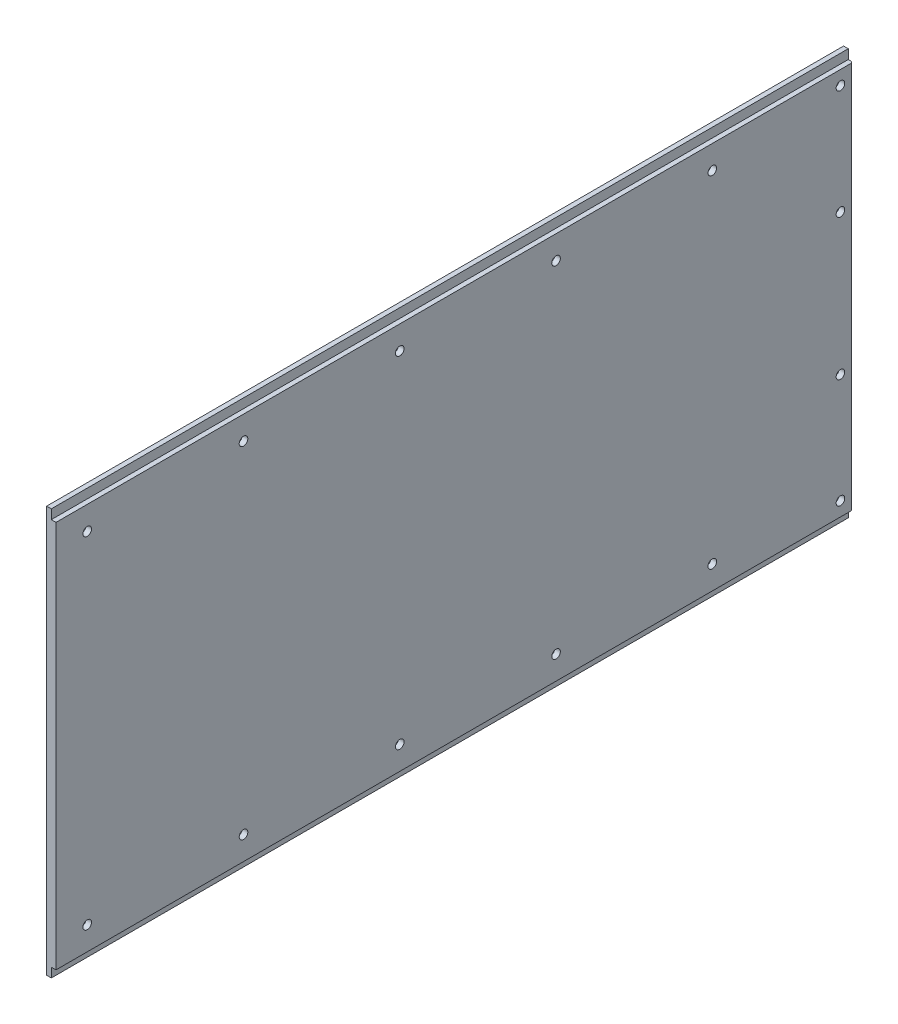
SolidWorks part; units mm, degrees
material "1060 Legierung"
ref_plane "Front Plane" through (0, 0, 0) normal (0, 0, 1) x (1, 0, 0)
ref_plane "Top Plane" through (0, 0, 0) normal (0, 1, 0) x (1, 0, 0)
ref_plane "Right Plane" through (0, 0, 0) normal (1, 0, 0) x (0, 0, -1)
sketch "Sketch1" plane through (0, 0, 0) normal (1, 0, 0) x (0, 0, -1)
  line L0 (0, 0) -> (59.3183, 0) construction
  line L1 (0, 28.1909) -> (0, -28.8956) construction
  line L2 (-255, 130) -> (255, 130)
  line L3 (255, 130) -> (255, -130)
  line L4 (255, -130) -> (-255, -130)
  line L5 (-255, -130) -> (-255, 130)
  dimension "D1" = 510
  dimension "D2" = 260
extrude "Boss-Extrude1" add sketch "Sketch1" along normal blind 6
sketch "Skizze2" plane through (0, 0, 255) normal (0, 0, 1) x (1, 0, 0)
  line L0 (21.4169, 0) -> (-13.9476, 0) construction
  line L1 (3, 130) -> (3, 124)
  line L2 (6, -130) -> (3, -130)
  line L3 (6, -130) -> (6, -124)
  line L4 (6, -124) -> (3, -124)
  line L5 (3, -130) -> (3, -124)
  line L6 (6, 124) -> (3, 124)
  line L7 (6, 130) -> (6, 124)
  line L8 (6, 130) -> (3, 130)
  dimension "D1" = 6
  dimension "D2" = 3
extrude "Schnitt-Linear austragen1" cut sketch "Skizze2" against normal through all
hole_wizard "Formsenkung fur M5 Linsensenkschraube mit Schlitz1" positions "Skizze6" profile "Skizze5" countersink size "M5" standard "Din" end condition through all
sketch "Skizze6" plane through (0, 0, 0) normal (-1, 0, 0) x (0, 0, 1)
  line L0 (-472.3808, 0) -> (85.2194, 0) construction
  line L2 (-255, -130) -> (-255, 130) construction
  point P0 (-247, 115)
  point P2 (-247, 45)
  dimension "D1" = 45
  dimension "D2" = 115
  dimension "D3" = 8
  dimension "D4" = 8
sketch "Skizze5" plane through (0, 115, -247) normal (0, 1, 0) x (0, 0, 1)
  line L0 (0, 0) -> (0, 6)
  line L1 (0, 6) -> (2.75, 6)
  line L2 (2.75, 6) -> (2.75, 2.45)
  line L3 (2.75, 2.45) -> (5.2, 0)
  line L5 (5.2, 0) -> (0, 0)
  line L6 (-2.75, 2.45) -> (-5.2, 0) construction
  line L11 (0, -6.35) -> (0, 107.95) construction
  dimension "Bohrerdurchmesser" = 5.5
  dimension "Bohrungstiefe" = 6
  dimension "Senkdurchmesser (Oben)" = 10.4
  dimension "Senkwinkel (Oben)" = 90
mirror "Spiegeln1" about plane through (0, 0, 0) normal (0, 1, 0) of "Formsenkung fur M5 Linsensenkschraube mit Schlitz1"
chamfer "Chamfer1" distance 1 angle 45 1 edges at (6, 0, -255)
hole_wizard "CSK for M5 Countersunk Raised Head Screw1" positions "Sketch3" profile "Sketch2" countersink size "M5" standard "DIN" end condition through all
sketch "Sketch3" plane through (0, 0, 0) normal (-1, 0, 0) x (0, 0, 1)
  line L0 (255, -130) -> (-255, -130) construction
  line L1 (255, 130) -> (255, -130) construction
  point P0 (235, -109)
  dimension "D1" = 21
  dimension "D2" = 20
sketch "Sketch2" plane through (0, -109, 235) normal (0, 1, 0) x (0, 0, 1)
  line L0 (0, 0) -> (0, 6)
  line L1 (0, 6) -> (2.75, 6)
  line L2 (2.75, 6) -> (2.75, 2.45)
  line L3 (2.75, 2.45) -> (5.2, 0)
  line L5 (5.2, 0) -> (0, 0)
  line L6 (-2.75, 2.45) -> (-5.2, 0) construction
  line L11 (0, -6.35) -> (0, 107.95) construction
  dimension "Thru Hole Dia." = 5.5
  dimension "Thru Hole Depth" = 6
  dimension "Near C'Sink Dia." = 10.4
  dimension "Near C'Sink Angle" = 90
pattern_linear "LPattern1" count 5 spacing 100 along (0, 0, -1) of "CSK for M5 Countersunk Raised Head Screw1"
mirror "Mirror1" about plane through (0, 0, 0) normal (0, 1, 0) of "LPattern1", "CSK for M5 Countersunk Raised Head Screw1"
